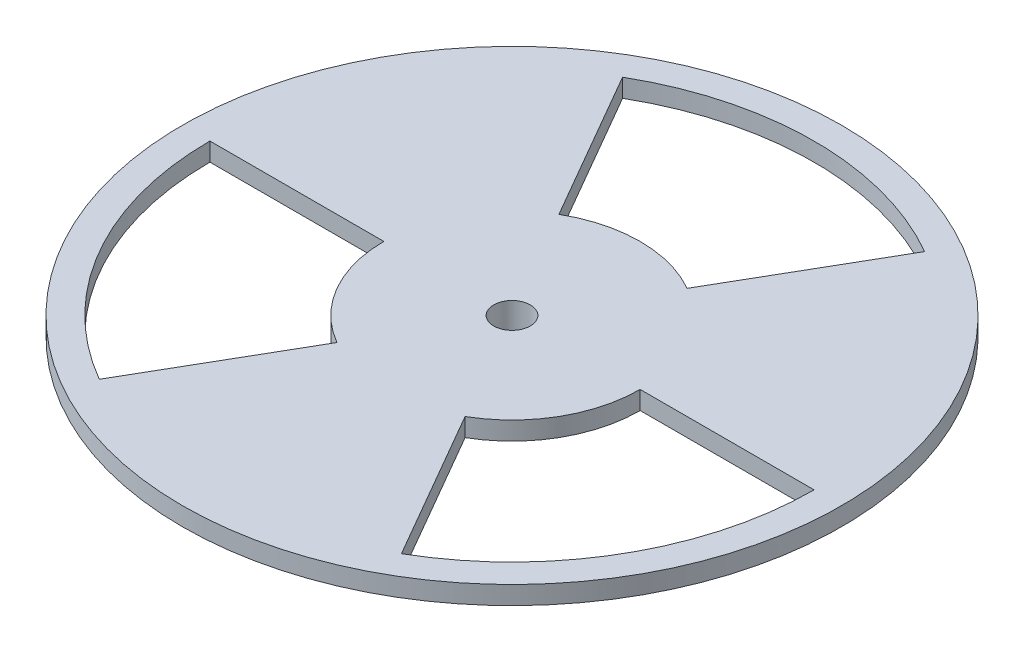
SolidWorks part; units mm, degrees
ref_plane "Front Plane" through (0, 0, 0) normal (0, 0, 1) x (1, 0, 0)
ref_plane "Top Plane" through (0, 0, 0) normal (0, 1, 0) x (1, 0, 0)
ref_plane "Right Plane" through (0, 0, 0) normal (1, 0, 0) x (0, 0, -1)
sketch "Sketch1" plane through (0, 0, 0) normal (0, 1, 0) x (1, 0, 0)
  circle A0 centre (0, 0) radius 18
  dimension "D1" = 36
extrude "Boss-Extrude1" add sketch "Sketch1" along normal blind 1
sketch "Sketch2" plane through (0, 0, 0) normal (0, -1, 0) x (1, 0, 0)
  circle A0 centre (0, 0) radius 2
  dimension "D1" = 4
extrude "Boss-Extrude2" add sketch "Sketch2" along normal blind 2
sketch "Sketch3" plane through (0, -2, 0) normal (0, -1, 0) x (1, 0, 0)
  circle A0 centre (0, 0) radius 1
  dimension "D1" = 2
extrude "Cut-Extrude1" cut sketch "Sketch3" against normal through all
sketch "Sketch4" plane through (0, 1, 0) normal (0, 1, 0) x (1, 0, 0)
  line L0 (-3.5, 6.0622) -> (-8.25, 14.2894)
  line L1 (3.5, 6.0622) -> (8.25, 14.2894)
  line L2 (0, 0) -> (0, 50000) construction
  line L3 (3.5, 6.0622) -> (0, 0) construction
  line L4 (0, 0) -> (-3.5, 6.0622) construction
  line L5 (7, 0) -> (16.5, 0)
  line L6 (3.5, -6.0622) -> (8.25, -14.2894)
  line L7 (-3.5, -6.0622) -> (-8.25, -14.2894)
  line L8 (-7, 0) -> (-16.5, 0)
  arc A0 (-8.25, 14.2894) -> (8.25, 14.2894) centre (0, 0) cw
  circle A1 centre (0, 0) radius 18 construction
  arc A2 (-3.5, 6.0622) -> (3.5, 6.0622) centre (0, 0) cw
  arc A3 (16.5, 0) -> (8.25, -14.2894) centre (0, 0) cw
  arc A4 (7, 0) -> (3.5, -6.0622) centre (0, 0) cw
  arc A5 (-8.25, -14.2894) -> (-16.5, 0) centre (0, 0) cw
  arc A6 (-3.5, -6.0622) -> (-7, 0) centre (0, 0) cw
  dimension "D4" = 7
  dimension "D1" = 30
  dimension "D2" = 30
  dimension "D3" = 1.5
  dimension "D5" = 3
extrude "Cut-Extrude2" cut sketch "Sketch4" against normal up to next contours L0 A0 L1 A2
equation "\"D2@Sketch4\"=\"D1@Sketch4\""
